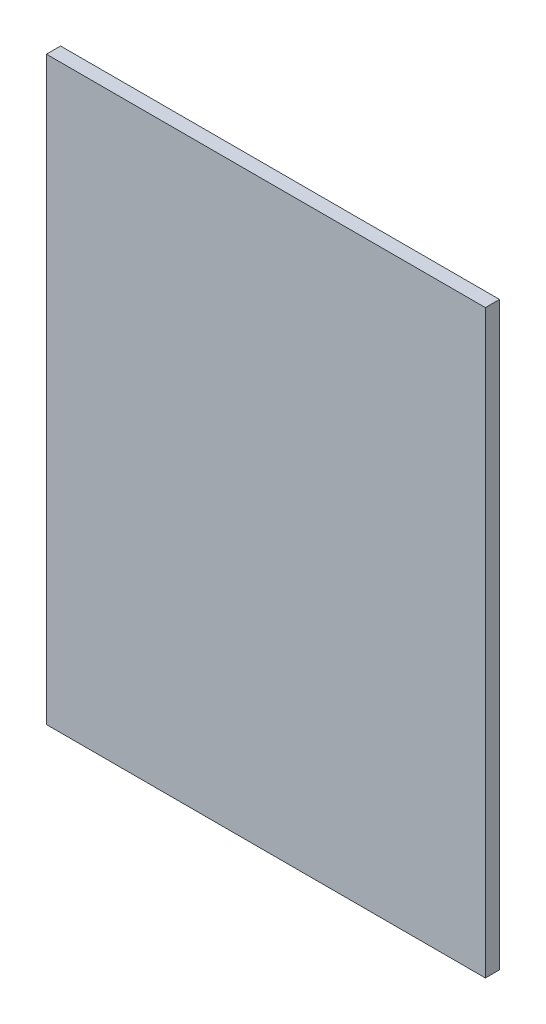
SolidWorks part; units mm, degrees
ref_plane "Plan de face" through (0, 0, 0) normal (0, 0, 1) x (1, 0, 0)
ref_plane "Plan de dessus" through (0, 0, 0) normal (0, 1, 0) x (1, 0, 0)
ref_plane "Plan de droite" through (0, 0, 0) normal (1, 0, 0) x (0, 0, -1)
sketch "Esquisse1" plane through (0, 0, 0) normal (0, 0, 1) x (1, 0, 0)
  line L1 (0, 0) -> (-310, 0)
  line L2 (0, 0) -> (0, 410)
  line L3 (0, 410) -> (-310, 410)
  line L4 (-310, 0) -> (-310, 410)
  dimension "D1" = 410
  dimension "D2" = 310
extrude "Boss.-Extru.1" add sketch "Esquisse1" along normal blind 10
